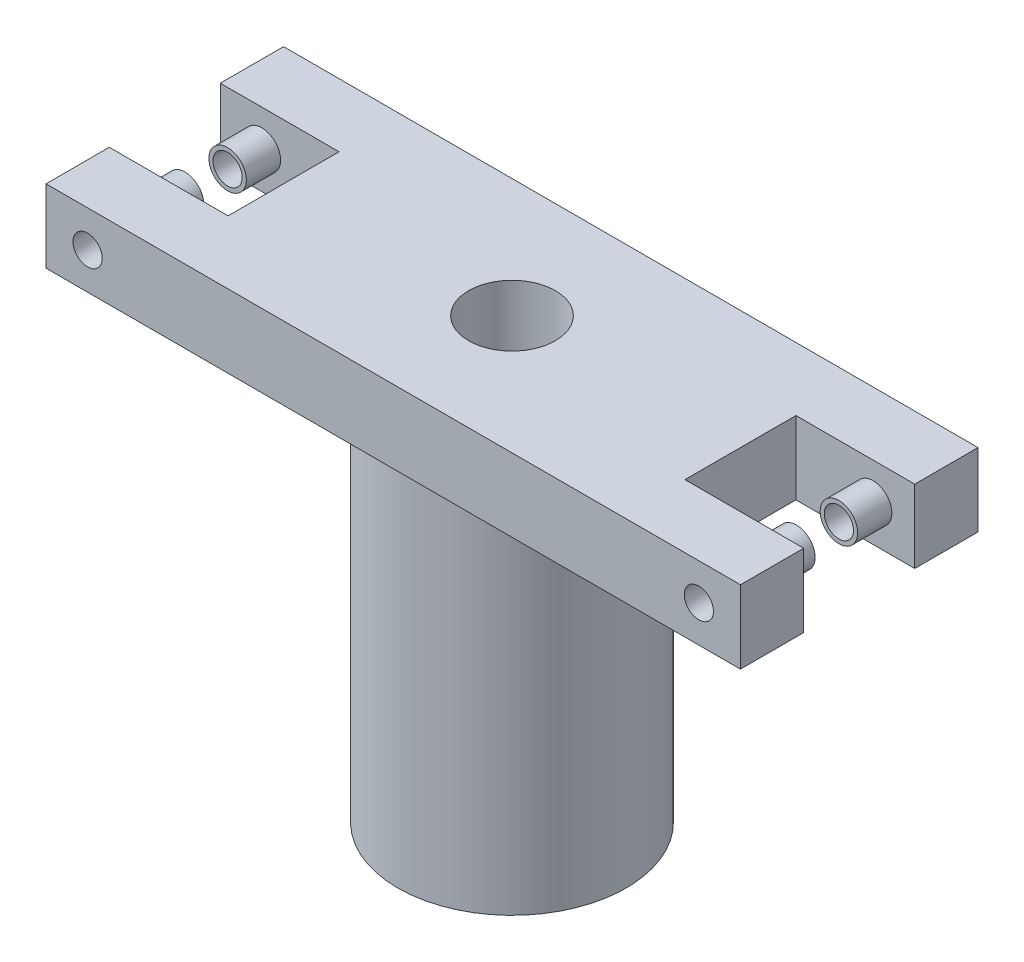
SolidWorks part; units mm, degrees
ref_plane "前视基准面" through (0, 0, 0) normal (0, 0, 1) x (1, 0, 0)
ref_plane "上视基准面" through (0, 0, 0) normal (0, 1, 0) x (1, 0, 0)
ref_plane "右视基准面" through (0, 0, 0) normal (1, 0, 0) x (0, 0, -1)
sketch "草图10" plane through (0, 0, 0) normal (0, 1, 0) x (1, 0, 0)
  circle A0 centre (0, 0) radius 12.5
  dimension "D1" = 25
extrude "凸台-拉伸5" add sketch "草图10" along normal blind 40
sketch "草图11" plane through (0, 0, 0) normal (0, -1, 0) x (-1, 0, 0)
  line L1 (5.74, -4.5426) -> (6.804, 2.6996)
  line L2 (6.804, 2.6996) -> (1.064, 7.2423)
  line L3 (1.064, 7.2423) -> (-5.74, 4.5426)
  line L4 (-5.74, 4.5426) -> (-6.804, -2.6996)
  line L5 (-6.804, -2.6996) -> (-1.064, -7.2423)
  line L6 (-1.064, -7.2423) -> (5.74, -4.5426)
  circle A0 centre (0, 0) radius 6.3393 construction
extrude "切除-拉伸1" cut sketch "草图11" against normal blind 11
sketch "草图12" plane through (0, 40, 0) normal (0, 1, 0) x (1, 0, 0)
  circle A0 centre (0, 0) radius 4.75
extrude "切除-拉伸2" cut sketch "草图12" against normal blind 18
sketch "草图13" plane through (0, 22, 0) normal (0, 1, 0) x (1, 0, 0)
  circle A0 centre (0, 0) radius 2.1
extrude "切除-拉伸3" cut sketch "草图13" against normal blind 20
sketch "草图14" plane through (0, 40, 0) normal (0, 1, 0) x (1, 0, 0)
  line L1 (38, -13) -> (-38, -13)
  line L2 (38, -13) -> (38, 13)
  line L3 (38, 13) -> (-38, 13)
  line L4 (-38, -13) -> (-38, 13)
  line L5 (0, 13) -> (0, -13) construction
  line L6 (38, 0) -> (-38, 0) construction
  point P0 (0, 0)
extrude "凸台-拉伸8" add sketch "草图14" along normal blind 8
sketch "草图15" plane through (0, 48, 0) normal (0, 1, 0) x (1, 0, 0)
  circle A0 centre (0, 0) radius 4.75
extrude "切除-拉伸4" cut sketch "草图15" against normal blind 8
sketch "草图16" plane through (0, 0, 13) normal (0, 0, 1) x (1, 0, 0)
  circle A0 centre (-33.45, 44) radius 1.6
  circle A1 centre (33.45, 44) radius 1.6
extrude "切除-拉伸5" cut sketch "草图16" against normal blind 26
sketch "草图17" plane through (0, 40, 0) normal (0, -1, 0) x (1, 0, 0)
  line L0 (38, 13) -> (38, -13) construction
  line L1 (25, 6.075) -> (38, 6.075)
  line L2 (25, 6.075) -> (25, -6.075)
  line L3 (25, -6.075) -> (38, -6.075)
  line L4 (38, 6.075) -> (38, -6.075)
  line L5 (-38, -13) -> (-38, 13) construction
  line L6 (-25, -6.075) -> (-38, -6.075)
  line L7 (-25, -6.075) -> (-25, 6.075)
  line L8 (-25, 6.075) -> (-38, 6.075)
  line L9 (-38, -6.075) -> (-38, 6.075)
extrude "切除-拉伸6" cut sketch "草图17" against normal blind 8
sketch "草图18" plane through (0, 0, 6.075) normal (0, 0, -1) x (-1, 0, 0)
  circle A0 centre (33.45, 44) radius 1.6
  circle A1 centre (33.45, 44) radius 2.05
  dimension "D1" = 4.1
extrude "凸台-拉伸9" add sketch "草图18" along normal blind 3.75
sketch "草图19" plane through (0, 0, -6.075) normal (0, 0, 1) x (1, 0, 0)
  circle A0 centre (-33.45, 44) radius 1.6
  circle A1 centre (-33.45, 44) radius 2.05
  dimension "D1" = 4.1
extrude "凸台-拉伸10" add sketch "草图19" along normal blind 3.75
sketch "草图20" plane through (0, 0, -6.075) normal (0, 0, 1) x (1, 0, 0)
  circle A0 centre (33.45, 44) radius 1.6
  circle A1 centre (33.45, 44) radius 2.05
  dimension "D1" = 4.1
extrude "凸台-拉伸11" add sketch "草图20" along normal blind 3.75
sketch "草图21" plane through (0, 0, 6.075) normal (0, 0, -1) x (-1, 0, 0)
  circle A0 centre (-33.45, 44) radius 1.6
  circle A1 centre (-33.45, 44) radius 2.05
  dimension "D1" = 4.1
extrude "凸台-拉伸12" add sketch "草图21" along normal blind 3.75
sketch "草图22" plane through (0, 0, -13) normal (0, 0, -1) x (-1, 0, 0)
  line L1 (-30.05, 44) -> (-31.75, 46.9445)
  line L2 (-31.75, 46.9445) -> (-35.15, 46.9445)
  line L3 (-35.15, 46.9445) -> (-36.85, 44)
  line L4 (-36.85, 44) -> (-35.15, 41.0555)
  line L5 (-35.15, 41.0555) -> (-31.75, 41.0555)
  line L6 (-31.75, 41.0555) -> (-30.05, 44)
  line L7 (36.85, 44) -> (35.15, 46.9445)
  line L8 (35.15, 46.9445) -> (31.75, 46.9445)
  line L9 (31.75, 46.9445) -> (30.05, 44)
  line L10 (30.05, 44) -> (31.75, 41.0555)
  line L11 (31.75, 41.0555) -> (35.15, 41.0555)
  line L12 (35.15, 41.0555) -> (36.85, 44)
  circle A0 centre (-33.45, 44) radius 2.9445 construction
  circle A1 centre (33.45, 44) radius 2.9445 construction
  dimension "D1" = 3.4
  dimension "D2" = 3.4
extrude "切除-拉伸7" cut sketch "草图22" against normal blind 2.5
